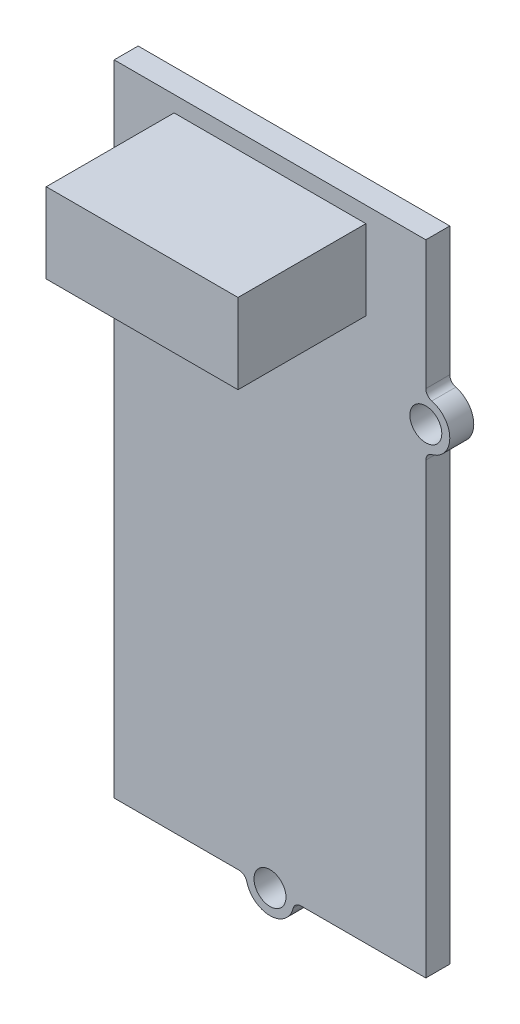
SolidWorks part; units mm, degrees
ref_plane "正面" through (0, 0, 0) normal (0, 0, 1) x (1, 0, 0)
ref_plane "平面" through (0, 0, 0) normal (0, 1, 0) x (1, 0, 0)
ref_plane "右側面" through (0, 0, 0) normal (1, 0, 0) x (0, 0, -1)
sketch "ｽｹｯﾁ1" plane through (0, 0, 0) normal (0, 0, 1) x (1, 0, 0)
  line L1 (-9.75, -20) -> (9.75, -20)
  line L2 (-9.75, -20) -> (-9.75, 20)
  line L3 (-9.75, 20) -> (9.75, 20)
  line L4 (9.75, -20) -> (9.75, 20)
  line L5 (-9.75, -20) -> (9.75, 20) construction
  line L6 (-9.75, 20) -> (9.75, -20) construction
  point P0 (0, 0)
  dimension "D1" = 19.5
  dimension "D2" = 40
extrude "ﾎﾞｽ - 押し出し1" add sketch "ｽｹｯﾁ1" along normal blind 1.5
sketch "ｽｹｯﾁ2" plane through (0, 0, 1.5) normal (0, 0, 1) x (1, 0, 0)
  line L0 (9.75, -20) -> (9.75, 20) construction
  line L1 (-9.75, 20) -> (-9.75, -20) construction
  line L2 (9.75, 20) -> (-9.75, 20) construction
  line L3 (-9.75, -20) -> (9.75, -20) construction
  circle A0 centre (9.75, 10) radius 1.5
  circle A1 centre (-9.75, 10) radius 1.5
  circle A2 centre (0, -20) radius 1.5
  dimension "D1" = 10
  dimension "D2" = 10
  dimension "D3" = 3
  dimension "D4" = 3
  dimension "D5" = 3
extrude "ﾎﾞｽ - 押し出し2" add sketch "ｽｹｯﾁ2" against normal blind 1.5
sketch "ｽｹｯﾁ3" plane through (0, 0, 1.5) normal (0, 0, 1) x (1, 0, 0)
  circle A0 centre (-9.75, 10) radius 1
  circle A1 centre (9.75, 10) radius 1
  circle A2 centre (0, -20) radius 1
  dimension "D1" = 2
  dimension "D2" = 2
  dimension "D3" = 2
extrude "ｶｯﾄ - 押し出し1" cut sketch "ｽｹｯﾁ3" against normal blind 1.5
fillet "ﾌｨﾚｯﾄ1" radius 0.5 6 edges at (-9.75, 11.5, 0.75) (-9.75, 8.5, 0.75) (9.75, 8.5, 0.75) (9.75, 11.5, 0.75) (-1.5, -20, 0.75) (1.5, -20, 0.75)
sketch "ｽｹｯﾁ4" plane through (0, 0, 1.5) normal (0, 0, 1) x (1, 0, 0)
  line L0 (9.75, 20) -> (-9.75, 20) construction
  line L1 (-6, 19) -> (6, 19)
  line L2 (-6, 19) -> (-6, 14)
  line L3 (-6, 14) -> (6, 14)
  line L4 (6, 19) -> (6, 14)
  point P6 (0, 19)
  point P7 (0, 20)
  dimension "D1" = 1
  dimension "D2" = 12
  dimension "D3" = 0
  dimension "D4" = 5
extrude "ﾎﾞｽ - 押し出し3" add sketch "ｽｹｯﾁ4" along normal blind 8
